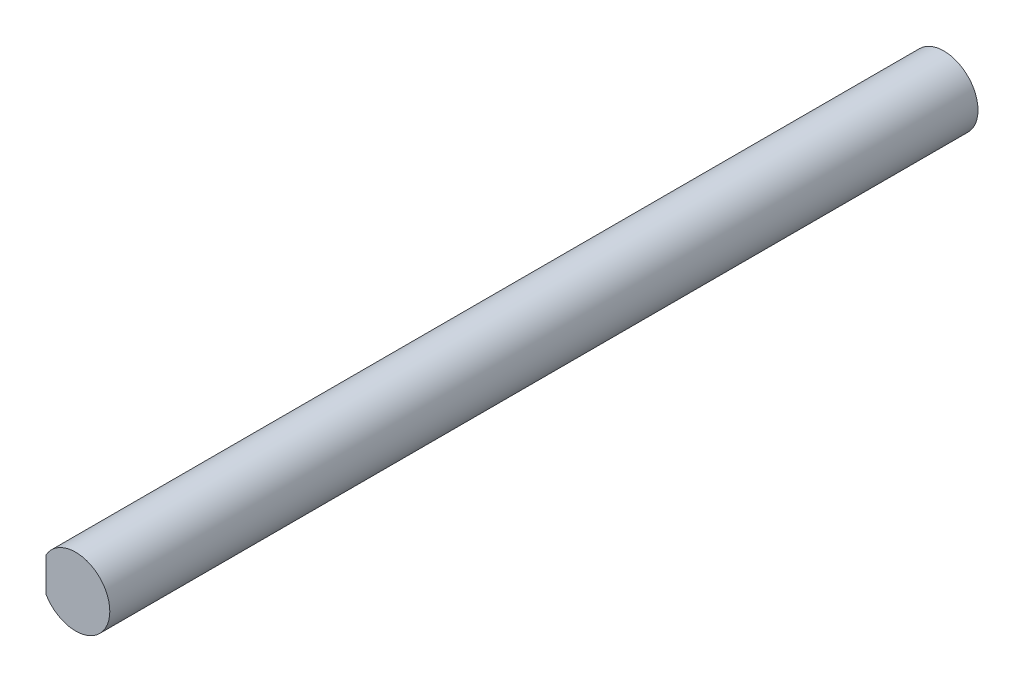
SolidWorks part; units mm, degrees
ref_plane "Front Plane" through (0, 0, 0) normal (0, 0, 1) x (1, 0, 0)
ref_plane "Top Plane" through (0, 0, 0) normal (0, 1, 0) x (1, 0, 0)
ref_plane "Right Plane" through (0, 0, 0) normal (1, 0, 0) x (0, 0, -1)
sketch "Sketch1" plane through (0, 0, 0) normal (0, 0, 1) x (1, 0, 0)
  line L4 (-2.6, 0) -> (-2.6, 1.4967)
  line L5 (-2.6, 0) -> (-2.6, -1.4967)
  arc A2 (-2.6, -1.4967) -> (-2.6, 1.4967) centre (0, 0) ccw
  point P1 (3, 0)
  dimension "D1" = 6
  dimension "D2" = 5.6
extrude "Boss-Extrude1" add sketch "Sketch1" along normal blind 76.2
